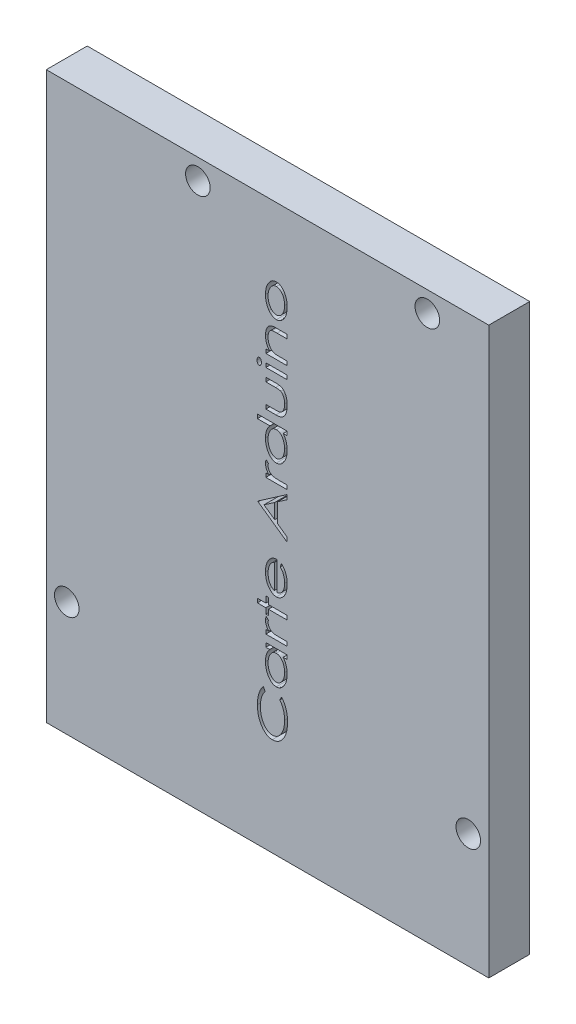
SolidWorks part; units mm, degrees
ref_plane "Plan de face" through (0, 0, 0) normal (0, 0, 1) x (1, 0, 0)
ref_plane "Plan de dessus" through (0, 0, 0) normal (0, 1, 0) x (1, 0, 0)
ref_plane "Plan de droite" through (0, 0, 0) normal (1, 0, 0) x (0, 0, -1)
sketch "Esquisse1" plane through (0, 0, 0) normal (0, 0, 1) x (1, 0, 0)
  line L1 (0, 0) -> (-54, 0)
  line L2 (0, 0) -> (0, 69)
  line L3 (0, 69) -> (-54, 69)
  line L4 (-54, 0) -> (-54, 69)
  dimension "D1" = 69
  dimension "D2" = 54
extrude "Extrusion1" add sketch "Esquisse1" along normal blind 5
sketch "Esquisse2" plane through (0, 0, 5) normal (0, 0, 1) x (1, 0, 0)
  line L0 (-24.6445, 62.9511) -> (-24.6445, 9.5726) construction
  text T0 "Carte Arduino " font "Century Gothic" height 3.5
extrude "Enlèv. mat.-Extru.1" cut sketch "Esquisse2" against normal blind 2
sketch "Esquisse3" plane through (0, 0, 5) normal (0, 0, 1) x (1, 0, 0)
  line L0 (0, 0) -> (0, 69) construction
  line L1 (0, 69) -> (-54, 69) construction
  line L3 (-54, 0) -> (0, 0) construction
  line L4 (-51.5, 14) -> (-2.5, 14) construction
  circle A0 centre (-35.5, 66.5) radius 1.5
  circle A1 centre (-7.5, 66.5) radius 1.5
  circle A2 centre (-51.5, 14) radius 1.5
  circle A3 centre (-2.5, 14) radius 1.5
  dimension "D1" = 3
  dimension "D2" = 3
  dimension "D3" = 3
  dimension "D4" = 3
  dimension "D13" = 52.5
  dimension "D5" = 7.5
  dimension "D6" = 28
  dimension "D7" = 2.5
  dimension "D8" = 2.5
  dimension "D9" = 2.5
  dimension "D10" = 49
  dimension "D11" = 14
  dimension "D12" = 14
extrude "Enlèv. mat.-Extru.2" cut sketch "Esquisse3" against normal blind 10
